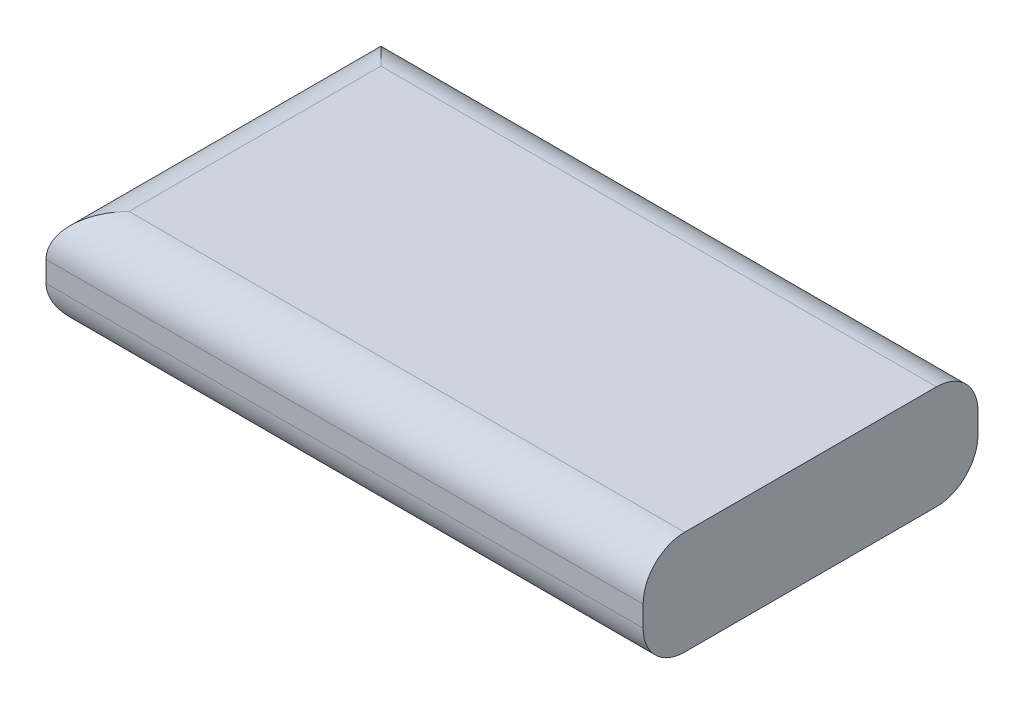
SolidWorks part; units mm, degrees
ref_plane "Front" through (0, 0, 0) normal (0, 0, 1) x (1, 0, 0)
ref_plane "Top" through (0, 0, 0) normal (0, 1, 0) x (1, 0, 0)
ref_plane "Right" through (0, 0, 0) normal (1, 0, 0) x (0, 0, -1)
sketch "草图1" plane through (0, 0, 0) normal (0, 1, 0) x (1, 0, 0)
  line L1 (-23, 12.9) -> (23, 12.9)
  line L2 (-23, 12.9) -> (-23, -12.9)
  line L3 (-23, -12.9) -> (23, -12.9)
  line L4 (23, 12.9) -> (23, -12.9)
  line L5 (-23, 12.9) -> (23, -12.9) construction
  line L6 (-23, -12.9) -> (23, 12.9) construction
  point P0 (0, 0)
extrude "凸台-拉伸1" add sketch "草图1" along normal blind 8 contours L1 L4 L3 L2
fillet "圆角1" radius 3.2 6 edges at (-23, 0, 0) (-23, 8, 0) (0, 0, -12.9) (0, 8, -12.9) (0, 0, 12.9) (0, 8, 12.9)
